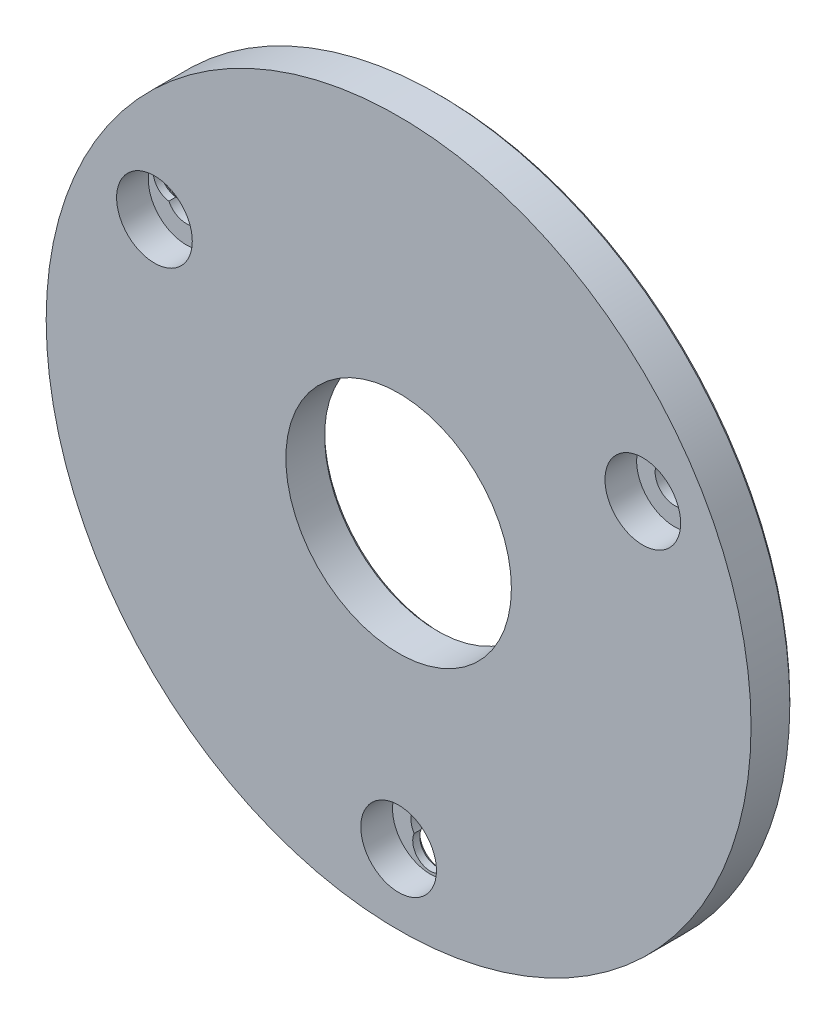
SolidWorks part; units mm, degrees
ref_plane "Piano frontale" through (0, 0, 0) normal (0, 0, 1) x (1, 0, 0)
ref_plane "Piano superiore" through (0, 0, 0) normal (0, 1, 0) x (1, 0, 0)
ref_plane "Piano destro" through (0, 0, 0) normal (1, 0, 0) x (0, 0, -1)
sketch "Schizzo1" plane through (0, 0, 0) normal (0, 0, 1) x (1, 0, 0)
  line L1 (0, 0) -> (0, 100) construction
  circle A0 centre (0, 0) radius 100
  circle A1 centre (0, 0) radius 32
  circle A2 centre (-73.6122, 42.5) radius 5
  circle A3 centre (73.6122, 42.5) radius 5
  circle A4 centre (0, -85) radius 5
  dimension "D1" = 64
  dimension "D2" = 200
extrude "Estrusione1" add sketch "Schizzo1" along normal blind 12
chamfer "Smusso1" distance 1 angle 45 5 edges at (100, 0, 0) (5, -85, 0) (-68.6122, 42.5, 0) (78.6122, 42.5, 0) (32, 0, 0)
hole_wizard "M10 Foro lamato per vite a testa esagonale (parzialmente filettata)2" positions "Schizzo6" profile "Schizzo7" counterbore size "M10" standard "ISO" end condition through all
sketch "Schizzo6" plane through (-8.7762, -26.1292, 12) normal (0, 0, 1) x (1, 0, 0)
  line L0 (8.7762, 26.1292) -> (8.7762, 152.3443) construction
  line L2 (8.7762, 26.1292) -> (-120.193, 100.5896) construction
  line L4 (8.7762, 26.1292) -> (78.0582, 66.1292) construction
  line L6 (8.7762, 26.1292) -> (8.7762, -53.8708) construction
  point P0 (-60.5059, 66.1292)
  point P16 (8.7762, -53.8708)
  point P18 (78.0582, 66.1292)
sketch "Schizzo7" plane through (-69.2819, 40.0002, 12) normal (1, 0, 0) x (0, -1, 0)
  line L0 (0, 0) -> (0, 12)
  line L1 (0, 12) -> (5.5, 12)
  line L3 (5.5, 12) -> (5.5, 9)
  line L4 (5.5, 9) -> (10.7375, 9)
  line L5 (10.7375, 9) -> (10.7375, 0)
  line L7 (10.7375, 0) -> (0, 0)
  line L11 (0, -6.35) -> (0, 107.95) construction
  dimension "Thru Hole Dia." = 11
  dimension "Thru Hole Depth" = 12
  dimension "C'Bore Dia." = 21.475
  dimension "C'Bore Depth" = 9
